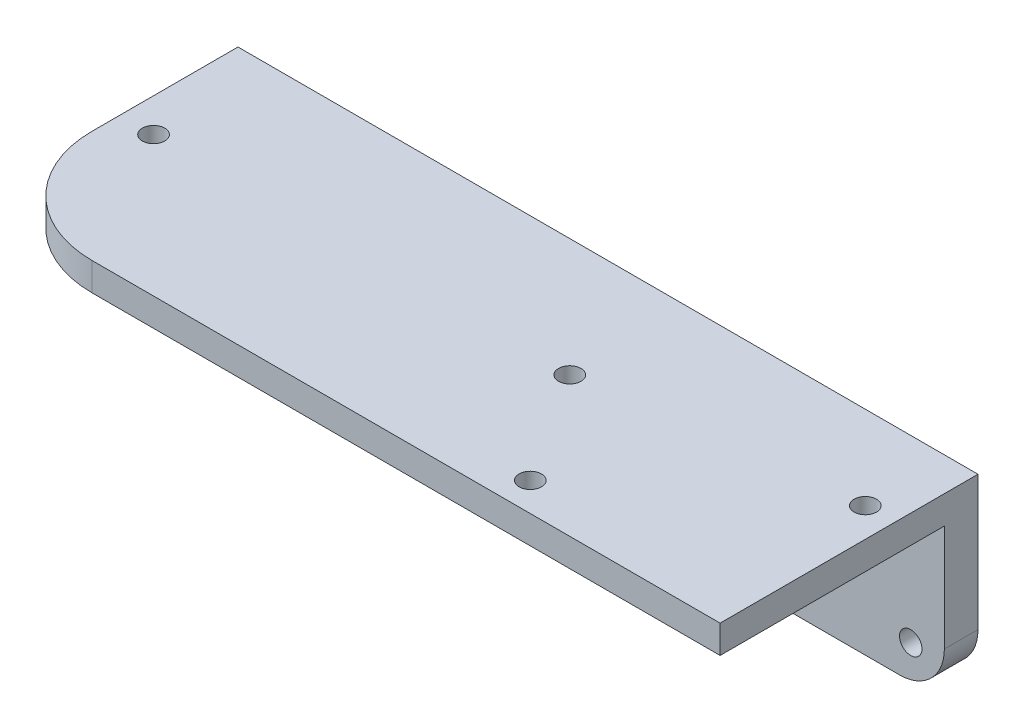
SolidWorks part; units mm, degrees
ref_plane "Plano frontal" through (0, 0, 0) normal (0, 0, 1) x (1, 0, 0)
ref_plane "Plano superior" through (0, 0, 0) normal (0, 1, 0) x (1, 0, 0)
ref_plane "Plano direito" through (0, 0, 0) normal (1, 0, 0) x (0, 0, -1)
sketch "Esboço21" plane through (0, 0, 0) normal (0, 0, 1) x (1, 0, 0)
  line L1 (-33, -8) -> (33, -8)
  line L2 (-33, -8) -> (-33, 8)
  line L3 (-33, 8) -> (33, 8)
  line L4 (33, -8) -> (33, 8)
  line L5 (-33, -8) -> (33, 8) construction
  line L6 (-33, 8) -> (33, -8) construction
  point P0 (0, 0)
  dimension "D1" = 66
  dimension "D2" = 16
extrude "Ressalto-extrusão1" add sketch "Esboço21" along normal blind 3
sketch "Esboço22" plane through (0, 0, 3) normal (0, 0, 1) x (1, 0, 0)
  line L0 (33, -8) -> (33, 8) construction
  line L1 (-33, 8) -> (33, 8)
  line L2 (-33, 8) -> (-33, 5.5)
  line L3 (-33, 5.5) -> (33, 5.5)
  line L4 (33, 8) -> (33, 5.5)
  dimension "D1" = 2.5
extrude "Ressalto-extrusão2" add sketch "Esboço22" along normal blind 20
sketch "Esboço23" plane through (0, 5.5, 0) normal (0, -1, 0) x (1, 0, 0)
  line L0 (-33, 3) -> (-30, 3) construction
  line L1 (-33, 3) -> (33, 3) construction
  line L2 (-30, 3) -> (-30, 10.53) construction
  line L3 (-30, 10.53) -> (7.12, 10.53) construction
  line L4 (33, 3) -> (30.4, 3) construction
  line L5 (30.4, 3) -> (30.4, 7.45) construction
  line L6 (30.4, 7.45) -> (13.51, 7.45) construction
  line L7 (13.51, 7.45) -> (13.51, 20.44) construction
  circle A0 centre (-30, 10.53) radius 1
  circle A1 centre (7.12, 10.53) radius 1
  circle A2 centre (30.4, 7.45) radius 1
  circle A3 centre (13.51, 20.44) radius 1
  dimension "D2" = 2
  dimension "D5" = 2
  dimension "D8" = 2
  dimension "D11" = 2
  dimension "D1" = 3
  dimension "D3" = 7.53
  dimension "D4" = 37.12
  dimension "D6" = 4.45
  dimension "D7" = 2.6
  dimension "D9" = 16.89
  dimension "D10" = 12.99
extrude "Corte-extrusão9" cut sketch "Esboço23" against normal through all
sketch "Esboço24" plane through (0, 0, 3) normal (0, 0, 1) x (1, 0, 0)
  line L0 (-33, 5.5) -> (-33, -8) construction
  line L2 (-33, -8) -> (33, -8) construction
  line L4 (-17.5532, -5) -> (-5.5532, -5)
  line L5 (-17.5532, -5) -> (-17.5532, 5)
  line L6 (-17.5532, 5) -> (-5.5532, 5)
  line L7 (-5.5532, -5) -> (-5.5532, 5)
  circle A0 centre (-30, -5) radius 1
  dimension "D6" = 2
  dimension "D1" = 3
  dimension "D2" = 3
  dimension "D3" = 10
  dimension "D4" = 12
  dimension "D5" = 3
extrude "Corte-extrusão10" cut sketch "Esboço24" against normal through all
fillet "Filete1" radius 10 1 edges at (-33, 6.75, 23)
fillet "Filete2" radius 4 2 edges at (33, -8, 1.5) (-33, -8, 1.5)
mirror "Espelhar1" about plane through (0, 0, 0) normal (1, 0, 0) of "Corte-extrusão10"
fillet "Filete3" radius 1 8 edges at (17.5532, -5, 1.5) (17.5532, 5, 1.5) (5.5532, -5, 1.5) (5.5532, 5, 1.5) (-5.5532, -5, 1.5) (-17.5532, -5, 1.5) (-5.5532, 5, 1.5) (-17.5532, 5, 1.5)
